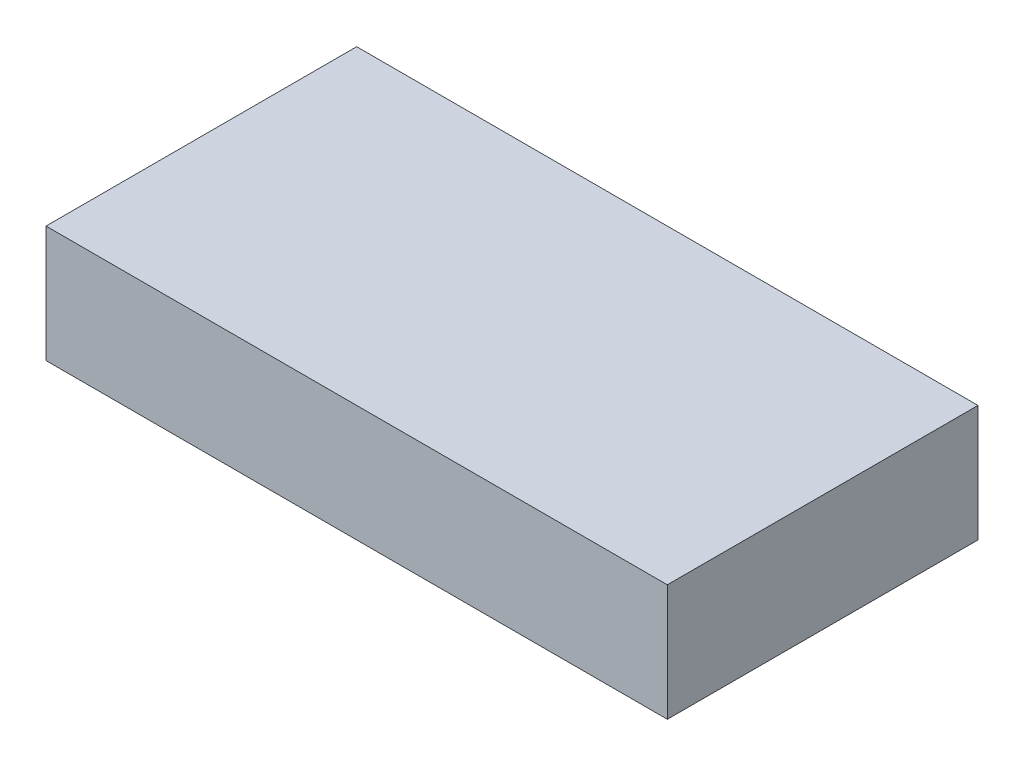
SolidWorks part; units mm, degrees
material "ABS"
ref_plane "Front Plane" through (0, 0, 0) normal (0, 0, 1) x (1, 0, 0)
ref_plane "Top Plane" through (0, 0, 0) normal (0, 1, 0) x (1, 0, 0)
ref_plane "Right Plane" through (0, 0, 0) normal (1, 0, 0) x (0, 0, -1)
sketch "Sketch1" plane through (0, 0, 0) normal (0, 0, 1) x (1, 0, 0)
  line L1 (-45.1303, 23.1413) -> (114.8697, 23.1413)
  line L2 (-45.1303, 23.1413) -> (-45.1303, -6.8587)
  line L3 (-45.1303, -6.8587) -> (114.8697, -6.8587)
  line L4 (114.8697, 23.1413) -> (114.8697, -6.8587)
  dimension "D1" = 160
  dimension "D2" = 30
extrude "Boss-Extrude1" add sketch "Sketch1" along normal blind 80
shell "Shell1" thickness 5
sketch "Sketch2" plane through (0, 0, 0) normal (0, 0, -1) x (-1, 0, 0)
  line L0 (45.1303, -6.8587) -> (-114.8697, -6.8587) construction
  line L1 (45.1303, 23.1413) -> (45.1303, -6.8587) construction
  circle A0 centre (30.1303, 7.8145) radius 4.1759
  dimension "D1" = 14.6732
  dimension "D2" = 15
extrude "Cut-Extrude1" cut sketch "Sketch2" against normal blind 15
pattern_linear "LPattern1" count 4 spacing 110 along (1, 0, 0) of "Cut-Extrude1"
